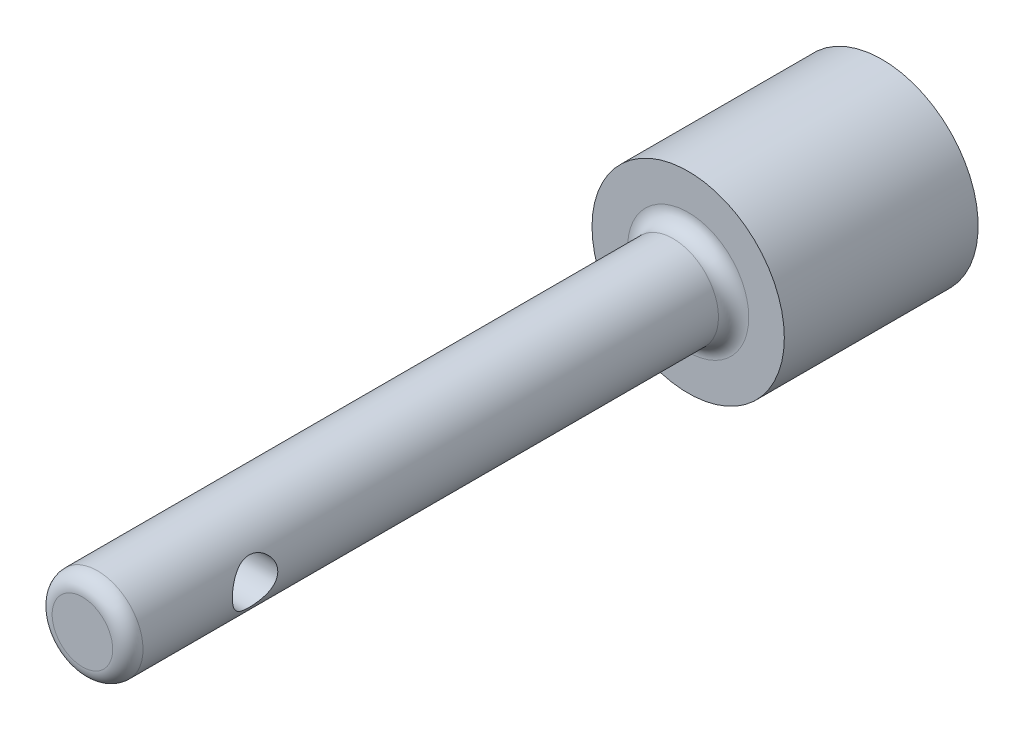
SolidWorks part; units mm, degrees
ref_plane "Front Plane" through (0, 0, 0) normal (0, 0, 1) x (1, 0, 0)
ref_plane "Top Plane" through (0, 0, 0) normal (0, 1, 0) x (1, 0, 0)
ref_plane "Right Plane" through (0, 0, 0) normal (1, 0, 0) x (0, 0, -1)
sketch "Sketch1" plane through (0, 0, 0) normal (0, 0, 1) x (1, 0, 0)
  circle A0 centre (0, 0) radius 3
  circle A1 centre (0, 0) radius 6.35
  dimension "D1" = 6
  dimension "D2" = 12.7
extrude "Boss-Extrude1" add sketch "Sketch1" along normal blind 11
sketch "Sketch2" plane through (0, 0, 11) normal (0, 0, 1) x (1, 0, 0)
  circle A0 centre (0, 0) radius 6.35 construction
  circle A1 centre (0, 0) radius 6.35
extrude "Boss-Extrude2" add sketch "Sketch2" along normal blind 2
sketch "Sketch3" plane through (0, 0, 13) normal (0, 0, 1) x (1, 0, 0)
  circle A0 centre (0, 0) radius 3
  dimension "D1" = 6
extrude "Boss-Extrude3" add sketch "Sketch3" along normal blind 40
sketch "Sketch4" plane through (0, 0, 0) normal (1, 0, 0) x (0, 0, -1)
  line L0 (0, 0) -> (-53, 0) construction
  line L1 (-53, 3) -> (-53, -3) construction
  line L2 (-13, 6.35) -> (-13, -6.35) construction
  circle A0 centre (-7, 0) radius 1.25
  dimension "D1" = 6
  dimension "D2" = 2.5
extrude "Cut-Extrude1" cut sketch "Sketch4" against normal blind 30 and the other way blind 4
cosmetic thread "Cosmetic Thread3" parameters "D2"=3.4
fillet "Fillet1" radius 1 1 edges at (3, 0, 13)
fillet "Fillet2" radius 1 1 edges at (3, 0, 53)
sketch "Sketch5" plane through (0, 0, 0) normal (1, 0, 0) x (0, 0, -1)
  line L0 (-53, 0) -> (0, 0) construction
  line L1 (-53, 2) -> (-53, -2) construction
  circle A0 centre (-44.6, 0) radius 1.5
  dimension "D1" = 3
  dimension "D2" = 8.4
extrude "Cut-Extrude2" cut sketch "Sketch5" against normal through all and the other way through all
sketch "Sketch6" plane through (0, 0, 0) normal (0, 0, -1) x (-1, 0, 0)
  circle A0 centre (0, 0) radius 6.35 construction
  circle A1 centre (0, 0) radius 6.35
extrude "Cut-Extrude3" cut sketch "Sketch6" against normal blind 0.2
